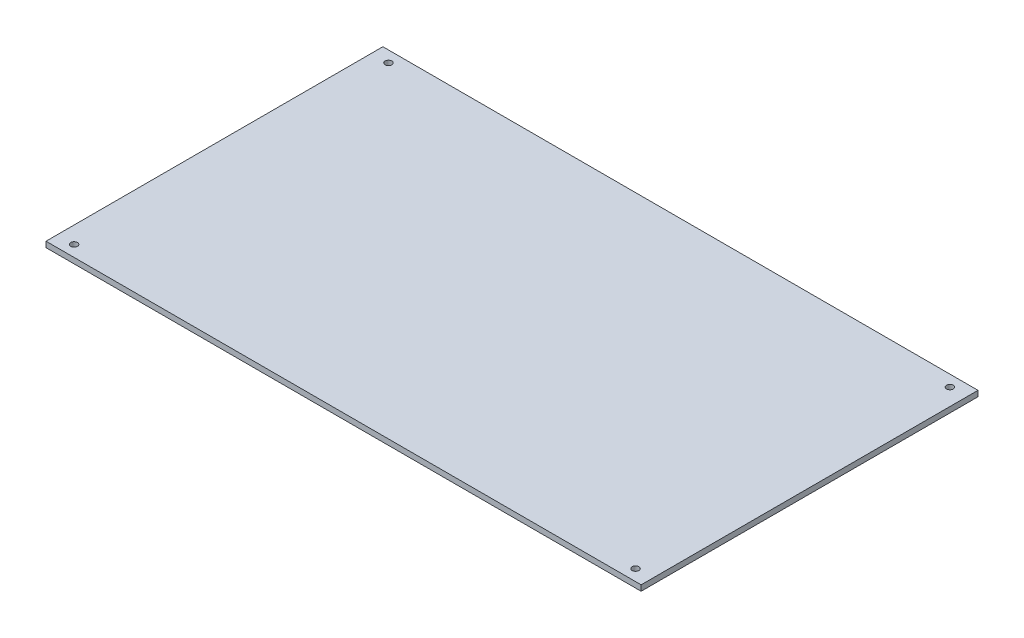
SolidWorks part; units mm, degrees
ref_plane "Alzado" through (0, 0, 0) normal (0, 0, 1) x (1, 0, 0)
ref_plane "Planta" through (0, 0, 0) normal (0, 1, 0) x (1, 0, 0)
ref_plane "Vista lateral" through (0, 0, 0) normal (1, 0, 0) x (0, 0, -1)
sketch "Croquis1" plane through (0, 0, 0) normal (0, 1, 0) x (1, 0, 0)
  line L1 (530, -300) -> (-530, -300)
  line L2 (530, -300) -> (530, 300)
  line L3 (530, 300) -> (-530, 300)
  line L4 (-530, -300) -> (-530, 300)
  line L5 (530, -300) -> (-530, 300) construction
  line L6 (530, 300) -> (-530, -300) construction
  point P0 (0, 0)
  dimension "D1" = 1060
  dimension "D2" = 600
extrude "Extruir1" add sketch "Croquis1" along normal blind 10
sketch "Croquis2" plane through (0, 10, 0) normal (0, 1, 0) x (1, 0, 0)
  line L0 (0, 0) -> (0, 300) construction
  line L1 (530, 300) -> (-530, 300) construction
  line L2 (0, 0) -> (530, 0) construction
  line L3 (530, -300) -> (530, 300) construction
  line L6 (530, 280) -> (-530, 280)
  line L7 (530, 280) -> (-530, 280) construction
  line L9 (-500, 300) -> (-500, -300)
  line L10 (-500, 300) -> (-500, -300) construction
  circle A0 centre (-500, 280) radius 6
  circle A1 centre (500, 280) radius 6
  circle A2 centre (500, -280) radius 6
  circle A3 centre (-500, -280) radius 6
  dimension "D3" = 12
  dimension "D1" = 20
  dimension "D2" = 30
extrude "Extruir2" cut sketch "Croquis2" against normal through all
